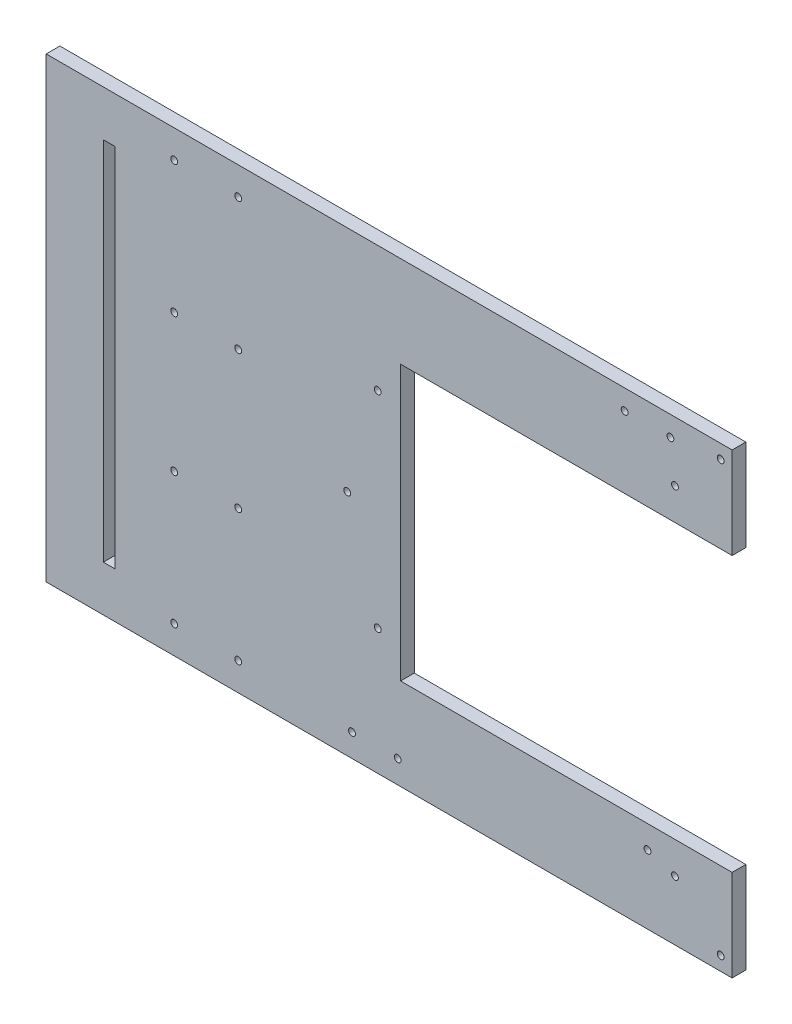
SolidWorks part; units mm, degrees
ref_plane "Front Plane" through (0, 0, 0) normal (0, 0, 1) x (1, 0, 0)
ref_plane "Top Plane" through (0, 0, 0) normal (0, 1, 0) x (1, 0, 0)
ref_plane "Right Plane" through (0, 0, 0) normal (1, 0, 0) x (0, 0, -1)
sketch "Sketch1" plane through (0, 0, 0) normal (0, 0, 1) x (1, 0, 0)
  line L1 (0, 0) -> (300, 0)
  line L2 (0, 0) -> (0, 200)
  line L3 (0, 200) -> (300, 200)
  line L4 (300, 0) -> (300, 200)
  dimension "D1" = 200
  dimension "D2" = 300
extrude "Boss-Extrude1" add sketch "Sketch1" along normal blind 6
sketch "Sketch2" plane through (0, 0, 0) normal (0, 0, 1) x (1, 0, 0)
  line L0 (300, 0) -> (300, 200) construction
  line L1 (300, 160) -> (155, 160)
  line L2 (300, 160) -> (300, 40)
  line L3 (300, 40) -> (155, 40)
  line L4 (155, 160) -> (155, 40)
  line L7 (0, 0) -> (300, 0) construction
  line L8 (300, 200) -> (0, 200) construction
  dimension "D1" = 40
  dimension "D2" = 40
  dimension "D3" = 145
extrude "Cut-Extrude1" cut sketch "Sketch2" along normal up to surface (6 mm away) contours L1 L4 L3 L2 up to face at (150, 100, 6)
sketch "Sketch3" plane through (0, 0, 0) normal (0, 0, 1) x (1, 0, 0)
  line L0 (300, 200) -> (0, 200) construction
  line L1 (25, 180) -> (30, 180)
  line L2 (25, 180) -> (25, 20)
  line L3 (25, 20) -> (30, 20)
  line L4 (30, 180) -> (30, 20)
  line L5 (0, 0) -> (300, 0) construction
  line L6 (0, 200) -> (0, 0) construction
  dimension "D1" = 20
  dimension "D2" = 20
  dimension "D3" = 25
  dimension "D4" = 5
extrude "Cut-Extrude2" cut sketch "Sketch3" along normal up to surface (6 mm away) up to face at (188.75, 100, 6)
hole_wizard "Ø3.0mm Press Dowel Hole1" positions "Sketch4" profile "Sketch5" hole size "Ø3.0" standard "AS"
sketch "Sketch4" plane through (42.4745, -126.5314, 6) normal (0, 0, 1) x (1, 0, 0)
  point P0 (220.5255, 156.5314)
  point P3 (102.5255, 181.5314)
  point P6 (102.5255, 271.5314)
  point P9 (89.1927, 226.5314)
  point P12 (210.5255, 317.7937)
  point P15 (230.5255, 317.7937)
  point P20 (252.5255, 320.4623)
  point P23 (232.5255, 300.4623)
  point P26 (252.5255, 132.6004)
  point P29 (232.5255, 152.6004)
  point P32 (111.2863, 136.5314)
  point P35 (91.2863, 136.5314)
  point P38 (41.5255, 196.4328)
  point P41 (13.5255, 196.4328)
  point P44 (41.5255, 138.768)
  point P47 (13.5255, 138.768)
  point P50 (41.5255, 256.6299)
  point P53 (13.5255, 256.6299)
  point P56 (41.5255, 314.2948)
  point P59 (13.5255, 314.2948)
sketch "Sketch5" plane through (263, 30, 6) normal (1, 0, 0) x (0, -1, 0)
  line L0 (0, 0) -> (0, 6.9013)
  line L1 (0, 6.9013) -> (1.5, 6)
  line L2 (1.5, 6) -> (1.5, 0)
  line L3 (1.5, 0) -> (0, 0)
  line L4 (0, 6.9013) -> (-1.5, 6) construction
  line L5 (0, -6.35) -> (0, 107.95) construction
  dimension "Hole Dia." = 3
  dimension "Hole Depth" = 6
  dimension "Drill Angle" = 118
